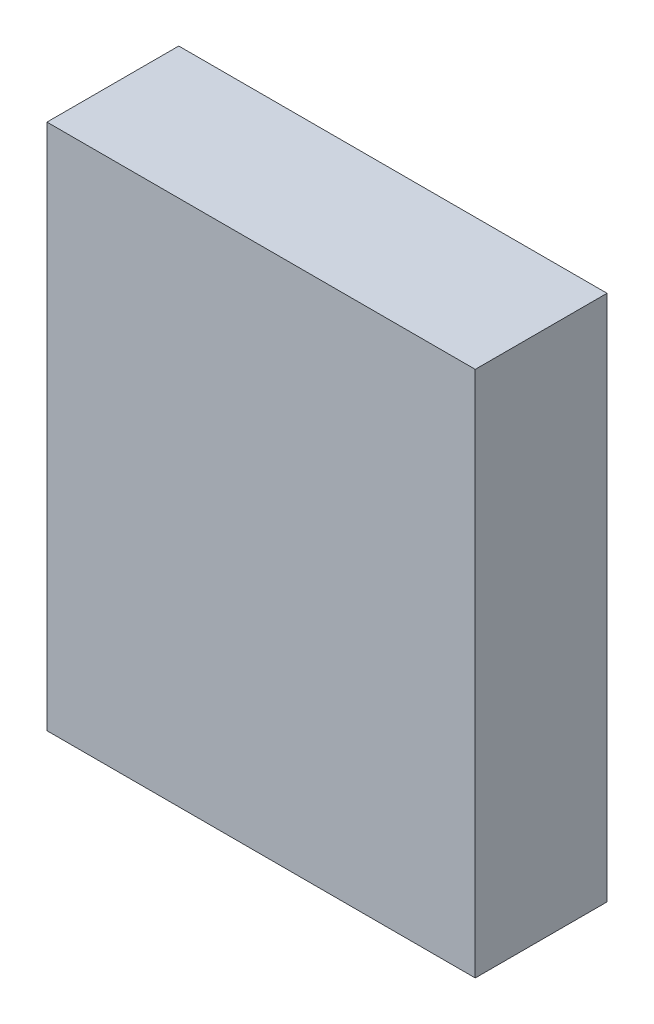
SolidWorks part; units mm, degrees
ref_plane "Piano frontale" through (0, 0, 0) normal (0, 0, 1) x (1, 0, 0)
ref_plane "Piano superiore" through (0, 0, 0) normal (0, 1, 0) x (1, 0, 0)
ref_plane "Piano destro" through (0, 0, 0) normal (1, 0, 0) x (0, 0, -1)
sketch "Schizzo1" plane through (0, 0, 0) normal (0, 0, 1) x (1, 0, 0)
  line L0 (-283.3288, 356.3208) -> (-218.3288, 356.3208)
  line L1 (-218.3288, 356.3208) -> (-218.3288, 276.3208)
  line L2 (-218.3288, 276.3208) -> (-283.3288, 276.3208)
  line L3 (-283.3288, 276.3208) -> (-283.3288, 356.3208)
  dimension "D1" = 65
  dimension "D2" = 80
extrude "Estrusione-Estrusione3" add sketch "Schizzo1" along normal blind 20
sketch "Schizzo4" plane through (0, 0, 0) normal (0, 0, -1) x (-1, 0, 0)
  line L0 (220.2851, 354.7611) -> (281.2851, 354.7611)
  line L1 (281.2851, 354.7611) -> (281.2851, 278.7611)
  line L2 (281.2851, 278.7611) -> (220.2851, 278.7611)
  line L3 (220.2851, 278.7611) -> (220.2851, 354.7611)
  dimension "D1" = 61
  dimension "D2" = 76
extrude "Taglio-Estrusione5" cut sketch "Schizzo4" against normal blind 18
sketch "Schizzo6" plane through (0, 276.3208, 0) normal (0, -1, 0) x (-1, 0, 0)
  line L0 (260.3304, 0.845) -> (249.3304, 0.845)
  line L1 (249.3304, 0.845) -> (249.3304, -7.655)
  line L2 (249.3304, -7.655) -> (260.3304, -7.655)
  line L3 (260.3304, -7.655) -> (260.3304, 0.845)
  point P2 (0, 0)
  dimension "D1" = 8.5
  dimension "D2" = 11
extrude "Taglio-Estrusione8" cut sketch "Schizzo6" against normal blind 3
sketch "Schizzo7" plane through (0, 0, 18) normal (0, 0, -1) x (-1, 0, 0)
  circle A0 centre (251.2243, 345.7465) radius 5.1828
extrude "Estrusione-Estrusione6" add sketch "Schizzo7" along normal blind 17 contours A0
